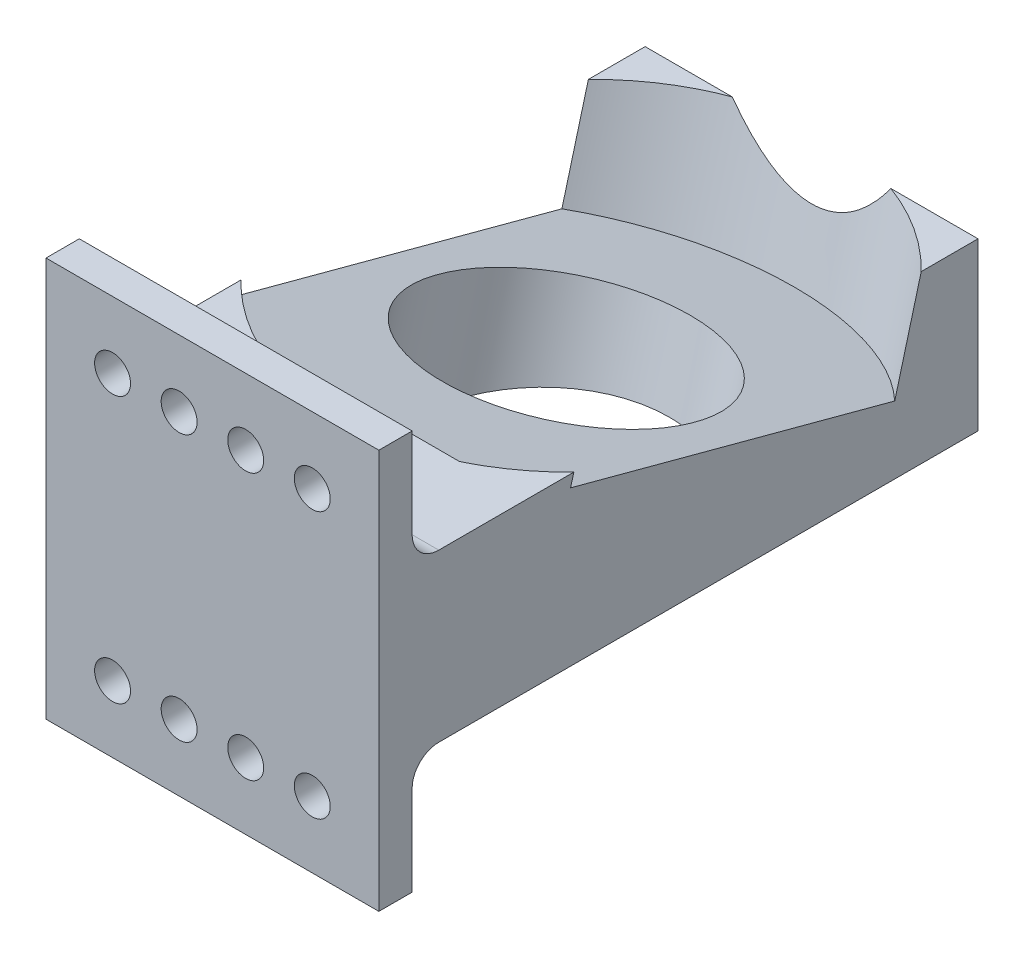
SolidWorks part; units mm, degrees
ref_plane "Front Plane" through (0, 0, 0) normal (0, 0, 1) x (1, 0, 0)
ref_plane "Top Plane" through (0, 0, 0) normal (0, 1, 0) x (1, 0, 0)
ref_plane "Right Plane" through (0, 0, 0) normal (1, 0, 0) x (0, 0, -1)
sketch "Sketch1" plane through (0, 0, 0) normal (1, 0, 0) x (0, 0, -1)
  line L1 (53.975, 15.875) -> (-53.975, 15.875)
  line L2 (53.975, 15.875) -> (53.975, -15.875)
  line L3 (53.975, -15.875) -> (-53.975, -15.875)
  line L4 (-53.975, 15.875) -> (-53.975, -15.875)
  line L5 (53.975, 15.875) -> (-53.975, -15.875) construction
  line L6 (53.975, -15.875) -> (-53.975, 15.875) construction
  point P0 (0, 0)
  dimension "D1" = 31.75
  dimension "D2" = 107.95
extrude "Boss-Extrude1" add sketch "Sketch1" along normal mid plane 63.5
sketch "Sketch2" plane through (0, 0, 0) normal (1, 0, 0) x (0, 0, -1)
  line L0 (0, -21.4654) -> (17.3249, 43.1921) construction
  line L1 (0, 0) -> (0, -41.4309) construction
  line L3 (30.7871, -1.0243) -> (21.7095, -34.9025)
  line L4 (21.7095, -34.9025) -> (-1.905, -28.575)
  line L5 (-1.905, -28.575) -> (15.9342, 38.0017)
  line L8 (53.975, -15.875) -> (53.975, 15.875) construction
  line L9 (-53.975, -15.875) -> (53.975, -15.875) construction
  line L10 (30.7871, -1.0243) -> (50.7214, -6.3656)
  line L11 (50.7214, -6.3656) -> (59.4829, 26.3328)
  line L12 (59.4829, 26.3328) -> (15.9342, 38.0017)
  point P7 (0, 0)
  dimension "D1" = 15
  dimension "D2" = 48.895
  dimension "D3" = 55.88
  dimension "D4" = 12.7
  dimension "D5" = 90.17
revolve "Cut-Revolve1" cut sketch "Sketch2" angle 360 about L0
sketch "Sketch3" plane through (0, 0, 53.975) normal (0, 0, 1) x (1, 0, 0)
  line L0 (31.75, 15.875) -> (31.75, -15.875) construction
  line L1 (-31.75, -38.1) -> (31.75, -38.1)
  line L2 (-31.75, -38.1) -> (-31.75, 38.1)
  line L3 (-31.75, 38.1) -> (31.75, 38.1)
  line L4 (31.75, -38.1) -> (31.75, 38.1)
  line L5 (-31.75, -38.1) -> (31.75, 38.1) construction
  line L6 (-31.75, 38.1) -> (31.75, -38.1) construction
  circle A0 centre (-19.05, 25.4) radius 3.429
  circle A1 centre (-6.35, 25.4) radius 3.429
  circle A2 centre (6.35, 25.4) radius 3.429
  circle A3 centre (19.05, 25.4) radius 3.429
  circle A4 centre (-6.35, -25.4) radius 3.429
  circle A5 centre (6.35, -25.4) radius 3.429
  circle A6 centre (19.05, -25.4) radius 3.429
  circle A7 centre (-19.05, -25.4) radius 3.429
  point P0 (0, 0)
  dimension "D2" = 6.858
  dimension "D1" = 76.2
  dimension "D3" = 12.7
  dimension "D4" = 12.7
  dimension "D5" = 4
  dimension "D6" = 2
extrude "Boss-Extrude2" add sketch "Sketch3" along normal blind 6.35
fillet "Fillet1" radius 5.08 2 edges at (0, 15.875, 53.975) (0, -15.875, 53.975)
